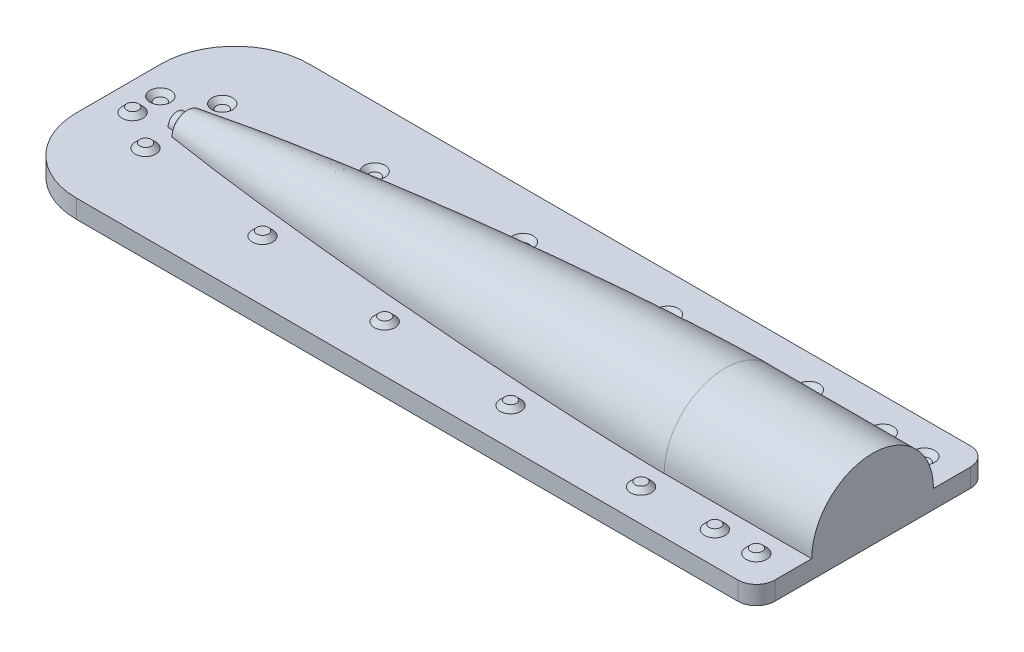
SolidWorks part; units mm, degrees
ref_plane "Front" through (0, 0, 0) normal (0, 0, 1) x (1, 0, 0)
ref_plane "Top" through (0, 0, 0) normal (0, 1, 0) x (1, 0, 0)
ref_plane "Right" through (0, 0, 0) normal (1, 0, 0) x (0, 0, -1)
other "von Karman body"
sketch "Sketch1" plane through (0, 0, 0) normal (0, 1, 0) x (1, 0, 0)
  line L0 (838.2, 83.82) -> (1041.4, 83.82)
  line L1 (1041.4, 83.82) -> (1055.402, 4.4107)
  line L2 (1055.7879, 0) -> (79.7661, 0)
  line L3 (96.6803, 12.7) -> (83.9803, 12.7)
  line L4 (96.6803, 12.7) -> (98.2259, 21.4654)
  line L5 (83.9803, 12.7) -> (80.7329, 4.8601)
  line L6 (0, 0) -> (1055.7879, 0) construction
  line L7 (83.9803, 12.7) -> (82.9291, 18.9624) construction
  line L8 (79.7661, 0) -> (79.7661, 6.839) construction
  circle A0 centre (3.2859, 0) radius 1.5875 construction
  arc A1 (80.7329, 4.8601) -> (79.7661, 0) centre (92.4661, 0) ccw
  arc A2 (1055.402, 4.4107) -> (1055.7879, 0) centre (1030.3879, 0) cw
  spline S0 degree 4 poles (0.0014, -0.0139) (0.0044, -0.0057) (0.0116, 0.0101) (0.0314, 0.0387) (0.0663, 0.0774) (0.1098, 0.1198) (0.1756, 0.1763) (0.2578, 0.2402) (0.43, 0.3617) (0.6491, 0.4956) (0.898, 0.6345) (1.1966, 0.7887) (1.4641, 0.9197) (1.9053, 1.1256) (2.6908, 1.4661) (4.1174, 2.0276) (6.8315, 2.9752) (11.8195, 4.4991) (21.1817, 6.9737) (37.5192, 10.6769) (65.2764, 16.0894) (103.3878, 22.4749) (149.5828, 29.2977) (200.9556, 36.0951) (252.4018, 42.3062) (303.9044, 48.03) (355.4522, 53.3298) (407.0382, 58.2429) (458.6575, 62.7928) (510.3066, 66.9901) (561.9831, 70.8361) (613.6852, 74.3214) (665.4118, 77.4242) (710.6933, 79.7692) (749.5207, 81.4699) (780.8317, 82.597) (801.9098, 83.2137) (819.2261, 83.6007) (830.0679, 83.7618) (835.4892, 83.8132) (838.2, 83.82) knots 0 0 0 0 0 0.000041 0.000082 0.000164 0.000247 0.000329 0.000493 0.000658 0.001245 0.001545 0.001844 0.002251 0.002657 0.003853 0.005902 0.009516 0.016281 0.028569 0.051794 0.088907 0.150314 0.211721 0.273128 0.334535 0.395942 0.457348 0.518755 0.580162 0.641569 0.702976 0.764383 0.825789 0.887196 0.9179 0.948603 0.974302 0.987151 1 1 1 1 1 construction
  spline S1 degree 4 poles (98.2259, 21.4654) (104.6543, 22.4927) (123.8878, 25.4864) (155.972, 30.1431) (200.9556, 36.0951) (252.4018, 42.3062) (303.9044, 48.03) (355.4522, 53.3298) (407.0382, 58.2429) (458.6575, 62.7928) (510.3066, 66.9901) (561.9831, 70.8361) (613.6852, 74.3214) (665.4118, 77.4242) (710.6933, 79.7692) (749.5207, 81.4699) (780.8317, 82.597) (801.9098, 83.2137) (819.2261, 83.6007) (830.0679, 83.7618) (835.4892, 83.8132) (838.2, 83.82) knots 0.119456 0.119456 0.119456 0.119456 0.119456 0.150314 0.211721 0.273128 0.334535 0.395942 0.457348 0.518755 0.580162 0.641569 0.702976 0.764383 0.825789 0.887196 0.9179 0.948603 0.974302 0.987151 1 1 1 1 1
  spline S2 degree 4 poles (0, 0) (0.003, 0.0082) (0.0102, 0.024) (0.03, 0.0526) (0.0649, 0.0913) (0.1084, 0.1337) (0.1742, 0.1902) (0.2565, 0.254) (0.4287, 0.3755) (0.6477, 0.5094) (0.8967, 0.6483) (1.1954, 0.8025) (1.4629, 0.9334) (1.9041, 1.1393) (2.6896, 1.4796) (4.1163, 2.0409) (6.8305, 2.9882) (11.8188, 4.5114) (21.1813, 6.9846) (37.5193, 10.6856) (65.2772, 16.0943) (103.3896, 22.4744) (149.5855, 29.2908) (200.9592, 36.0811) (252.4063, 42.285) (303.9097, 48.0016) (355.4582, 53.2943) (407.0449, 58.2003) (458.6648, 62.7429) (510.3146, 66.9331) (561.9916, 70.772) (613.6942, 74.2501) (665.4211, 77.3457) (710.703, 79.6843) (749.5307, 81.3797) (780.8418, 82.5024) (801.92, 83.1162) (819.2363, 83.5008) (830.0782, 83.6603) (835.4995, 83.711) (838.2103, 83.7174) knots 0 0 0 0 0 0.000041 0.000082 0.000164 0.000247 0.000329 0.000493 0.000658 0.001245 0.001545 0.001844 0.002251 0.002657 0.003853 0.005902 0.009516 0.016281 0.028569 0.051794 0.088907 0.150314 0.211721 0.273128 0.334535 0.395942 0.457348 0.518755 0.580162 0.641569 0.702976 0.764383 0.825789 0.887196 0.9179 0.948603 0.974302 0.987151 1 1 1 1 1 construction
  spline S3 degree 4 poles (0, 0) (0.003, 0.0082) (0.0102, 0.024) (0.03, 0.0526) (0.0649, 0.0913) (0.1084, 0.1337) (0.1742, 0.1902) (0.2565, 0.254) (0.4287, 0.3755) (0.6477, 0.5094) (0.8967, 0.6483) (1.1954, 0.8025) (1.4629, 0.9334) (1.9041, 1.1393) (2.6896, 1.4796) (4.1163, 2.0409) (6.8305, 2.9882) (11.8188, 4.5114) (21.1813, 6.9846) (37.5193, 10.6856) (58.8862, 14.849) (77.7757, 18.1421) (91.8621, 20.4493) (98.2259, 21.4654) knots 0 0 0 0 0 0.000041 0.000082 0.000164 0.000247 0.000329 0.000493 0.000658 0.001245 0.001545 0.001844 0.002251 0.002657 0.003853 0.005902 0.009516 0.016281 0.028569 0.051794 0.088907 0.119454 0.119454 0.119454 0.119454 0.119454 construction
  point P5 (0, 0)
  dimension "D6" = 3.175
  dimension "D9" = 25.4
  dimension "D10" = 12.7
  dimension "D1" = 12.7
  dimension "D2" = 100
  dimension "D3" = 203.2
  dimension "D4" = 6.35
  dimension "D5" = 838.2
  dimension "D7" = 67.5
  dimension "D8" = 80
  dimension "D11" = 83.82
  dimension "D12" = 12.7
revolve "main body" add sketch "Sketch1" angle 180 about L2
scale "Scale1" [suppressed]
sketch "Sketch2" plane through (0, 0, 0) normal (0, -1, 0) x (1, 0, 0)
  line L0 (1055.7879, 0) -> (1131.9879, 0) construction
  line L1 (1131.9879, -160.02) -> (3.5661, -160.02)
  line L2 (1131.9879, -160.02) -> (1131.9879, 160.02)
  line L3 (1131.9879, 160.02) -> (3.5661, 160.02)
  line L4 (3.5661, -160.02) -> (3.5661, 160.02)
  line L5 (1041.4, -83.82) -> (838.2, -83.82) construction
  arc A0 (1055.402, -4.4107) -> (1055.402, 4.4107) centre (1030.3879, 0) ccw construction
  arc A1 (80.7329, 4.8601) -> (80.7329, -4.8601) centre (92.4661, 0) ccw construction
  point P17 (79.7661, 0)
  dimension "D2" = 76.2
  dimension "D1" = 76.2
  dimension "D3" = 76.2
extrude "Boss-Extrude1" add sketch "Sketch2" along normal blind 25.4
fillet "Fillet1" radius 6.35 1 edges at (96.6803, 12.7, 0)
sketch "Sketch3" plane through (0, 0, 0) normal (0, 1, 0) x (1, 0, 0)
  line L0 (79.7661, 0) -> (3.5661, 0) construction
  line L3 (3.5661, -160.02) -> (3.5661, 160.02) construction
  line L4 (93.2155, -52.8176) -> (98.2259, -21.4654) construction
  line L5 (282.1124, -45.5691) -> (278.6203, -77.1265) construction
  line L6 (464.7467, -95.0932) -> (467.3901, -63.4534) construction
  line L7 (651.269, -108.3334) -> (653.1005, -76.6363) construction
  line L8 (838.1205, -115.5699) -> (838.2, -83.82) construction
  line L9 (1041.4, -83.82) -> (838.2, -83.82) construction
  line L10 (996.95, -115.57) -> (996.95, -83.82) construction
  line L11 (1055.7879, 0) -> (1131.9879, 0) construction
  line L12 (1131.9879, 160.02) -> (1131.9879, -160.02) construction
  line L13 (1079.6687, -49.6287) -> (1048.401, -44.1153) construction
  line L14 (1055.402, -4.4107) -> (1041.4, -83.82) construction
  line L15 (93.2155, -52.8176) -> (278.6203, -77.1265) construction
  line L16 (278.6203, -77.1265) -> (464.7467, -95.0932) construction
  line L17 (464.7467, -95.0932) -> (651.269, -108.3334) construction
  line L18 (651.269, -108.3334) -> (838.1205, -115.5699) construction
  line L19 (939.8, -115.57) -> (939.8, -83.82) construction
  circle A0 centre (996.95, -115.57) radius 14.2875
  circle A1 centre (838.1205, -115.5699) radius 14.2875
  circle A2 centre (93.2155, -52.8176) radius 14.2875
  circle A3 centre (464.7467, -95.0932) radius 14.2875
  circle A4 centre (278.6203, -77.1265) radius 14.2875
  circle A5 centre (651.269, -108.3334) radius 14.2875
  circle A6 centre (41.6661, -19.05) radius 14.2875
  circle A7 centre (1079.6687, -49.6287) radius 14.2875
  arc A9 (80.7329, 4.8601) -> (80.7329, -4.8601) centre (92.4661, 0) ccw construction
  arc A10 (1055.402, -4.4107) -> (1055.402, 4.4107) centre (1030.3879, 0) ccw construction
  circle A11 centre (939.8, -115.57) radius 14.2875
  spline S0 degree 4 poles (838.2, -83.82) (835.4892, -83.8132) (830.0679, -83.7618) (819.2261, -83.6007) (801.9098, -83.2137) (780.8317, -82.597) (749.5207, -81.4699) (710.6933, -79.7692) (665.4118, -77.4242) (613.6852, -74.3214) (561.9831, -70.8361) (510.3066, -66.9901) (458.6575, -62.7928) (407.0382, -58.2429) (355.4522, -53.3298) (303.9044, -48.03) (252.4018, -42.3062) (200.9556, -36.0951) (155.972, -30.1431) (123.8878, -25.4864) (104.6543, -22.4927) (98.2259, -21.4654) knots 0.119456 0.119456 0.119456 0.119456 0.119456 0.132305 0.145154 0.170853 0.201556 0.23226 0.293667 0.355073 0.41648 0.477887 0.539294 0.600701 0.662108 0.723514 0.784921 0.846328 0.907735 0.969142 1 1 1 1 1 construction
  point P48 (939.8, -83.82)
  dimension "D1" = 28.575
  dimension "D2" = 19.05
  dimension "D3" = 38.1
  dimension "D4" = 31.75
  dimension "D5" = 57.15
extrude "Boss-Extrude2" add sketch "Sketch3" along normal blind 6.35 draft 45
sketch "Sketch4" plane through (0, 0, 0) normal (0, 1, 0) x (1, 0, 0)
  line L0 (3.5661, 0) -> (1131.9879, 0) construction
  line L1 (3.5661, -160.02) -> (3.5661, 160.02) construction
  line L2 (1131.9879, 160.02) -> (1131.9879, -160.02) construction
  circle A0 centre (996.95, 115.57) radius 14.2875
  circle A1 centre (1079.6687, -49.6287) radius 14.2875
  circle A2 centre (1079.6687, -49.6287) radius 14.2875 construction
  circle A3 centre (41.6661, -19.05) radius 14.2875
  circle A4 centre (41.6661, -19.05) radius 14.2875 construction
  circle A5 centre (651.269, -108.3334) radius 14.2875
  circle A6 centre (651.269, -108.3334) radius 14.2875 construction
  circle A7 centre (278.6203, -77.1265) radius 14.2875
  circle A8 centre (278.6203, -77.1265) radius 14.2875 construction
  circle A9 centre (464.7467, -95.0932) radius 14.2875
  circle A10 centre (464.7467, -95.0932) radius 14.2875 construction
  circle A11 centre (93.2155, -52.8176) radius 14.2875
  circle A12 centre (93.2155, -52.8176) radius 14.2875 construction
  circle A13 centre (838.1205, -115.5699) radius 14.2875
  circle A14 centre (838.1205, -115.5699) radius 14.2875 construction
  circle A15 centre (996.95, -115.57) radius 14.2875
  circle A16 centre (996.95, -115.57) radius 14.2875 construction
  circle A17 centre (838.1205, 115.5699) radius 14.2875
  circle A18 centre (93.2155, 52.8176) radius 14.2875
  circle A19 centre (464.7467, 95.0932) radius 14.2875
  circle A20 centre (278.6203, 77.1265) radius 14.2875
  circle A21 centre (651.269, 108.3334) radius 14.2875
  circle A22 centre (41.6661, 19.05) radius 14.2875
  circle A23 centre (1079.6687, 49.6287) radius 14.2875
  circle A24 centre (939.8, 115.57) radius 14.2875
  circle A25 centre (939.8, -115.57) radius 14.2875
  circle A26 centre (939.8, -115.57) radius 14.2875 construction
  dimension "D1" = 0
  dimension "D2" = 0
  dimension "D3" = 0
  dimension "D4" = 0
  dimension "D5" = 0
  dimension "D6" = 0
  dimension "D7" = 0
  dimension "D8" = 0
  dimension "D9" = 0
extrude "Cut-Extrude1" cut sketch "Sketch4" against normal blind 6.35 draft 45
sketch "Sketch5" plane through (1131.9879, 0, 0) normal (1, 0, 0) x (0, 0, -1)
  line L1 (228.0392, 118.5985) -> (-235.7612, 118.5985)
  line L2 (228.0392, 118.5985) -> (228.0392, -74.0127)
  line L3 (228.0392, -74.0127) -> (-235.7612, -74.0127)
  line L4 (-235.7612, 118.5985) -> (-235.7612, -74.0127)
extrude "Cut-Extrude2" cut sketch "Sketch5" along direction (-1, 0, 0) on the side against the normal up to vertex (90.5879 mm away)
fillet "Fillet2" radius 25.4 2 edges at (1041.4, -12.7, -160.02) (1041.4, -12.7, 160.02)
fillet "Fillet3" radius 101.6 2 edges at (3.5661, -12.7, 160.02) (3.5661, -12.7, -160.02)
